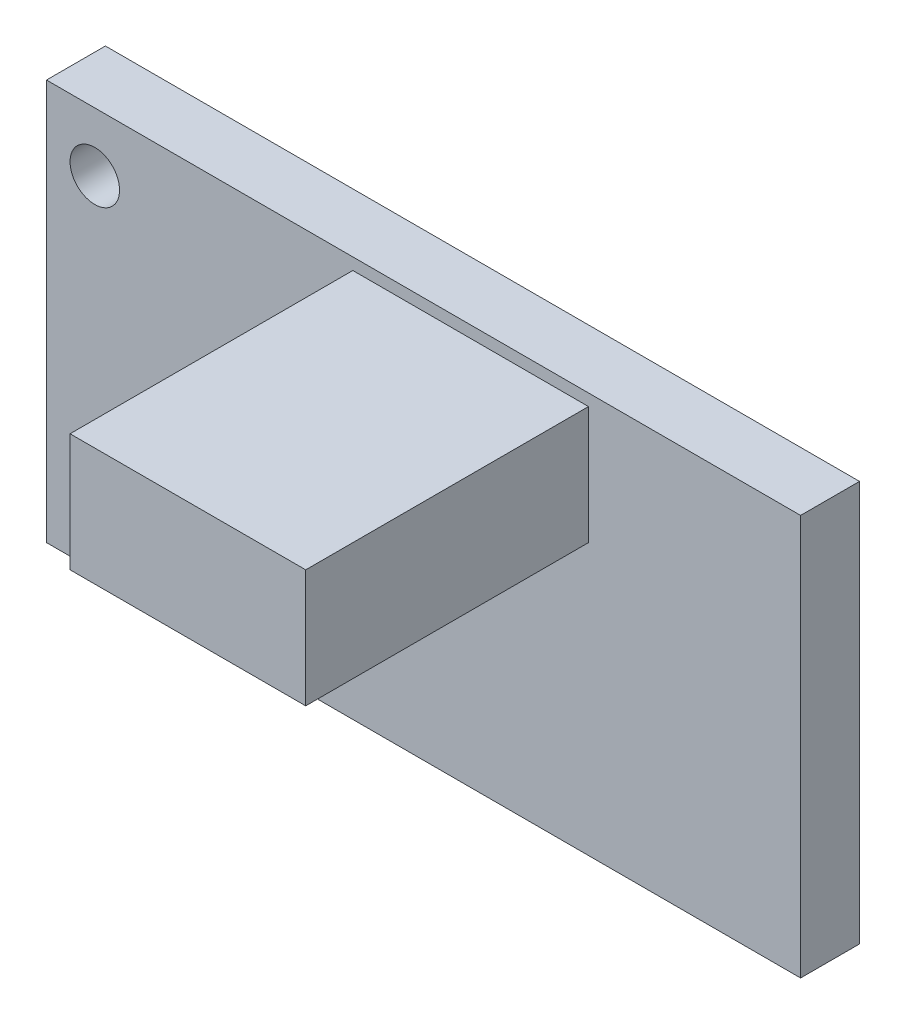
SolidWorks part; units mm, degrees
ref_plane "Plano frontal" through (0, 0, 0) normal (0, 0, 1) x (1, 0, 0)
ref_plane "Plano superior" through (0, 0, 0) normal (0, 1, 0) x (1, 0, 0)
ref_plane "Plano direito" through (0, 0, 0) normal (1, 0, 0) x (0, 0, -1)
sketch "Sketch1" plane through (0, 0, 0) normal (0, 0, 1) x (1, 0, 0)
  line L1 (0, 0) -> (32, 0)
  line L2 (0, 0) -> (0, -17)
  line L3 (0, -17) -> (32, -17)
  line L4 (32, 0) -> (32, -17)
  line L5 (0, 0) -> (32, -17) construction
  line L6 (0, -17) -> (32, 0) construction
  point P4 (16, -8.5)
  dimension "D1" = 32
  dimension "D2" = 17
extrude "Boss-Extrude1" add sketch "Sketch1" along normal blind 2.5
sketch "Sketch2" plane through (0, 0, 2.5) normal (0, 0, 1) x (1, 0, 0)
  line L0 (0, 0) -> (0, -17) construction
  line L1 (13, -0.5) -> (23, -0.5)
  line L2 (13, -0.5) -> (13, -5.5)
  line L3 (13, -5.5) -> (23, -5.5)
  line L4 (23, -0.5) -> (23, -5.5)
  line L5 (13, -0.5) -> (23, -5.5) construction
  line L6 (13, -5.5) -> (23, -0.5) construction
  line L7 (32, 0) -> (0, 0) construction
  point P4 (18, -3)
  dimension "D1" = 5
  dimension "D2" = 10
  dimension "D3" = 13
  dimension "D4" = 0.5
extrude "Boss-Extrude2" add sketch "Sketch2" along normal blind 12
sketch "Sketch3" plane through (0, 0, 2.5) normal (0, 0, 1) x (1, 0, 0)
  line L0 (0, 0) -> (0, -17) construction
  line L2 (0, -17) -> (32, -17) construction
  circle A0 centre (2.05, -2.5) radius 1.05
  circle A1 centre (2.05, -14.5) radius 1.05
  dimension "D1" = 2.1
  dimension "D2" = 2.1
  dimension "D6" = 2.05
  dimension "D3" = 12
  dimension "D4" = 2.05
  dimension "D5" = 2.5
extrude "Cut-Extrude1" cut sketch "Sketch3" against normal blind 12
